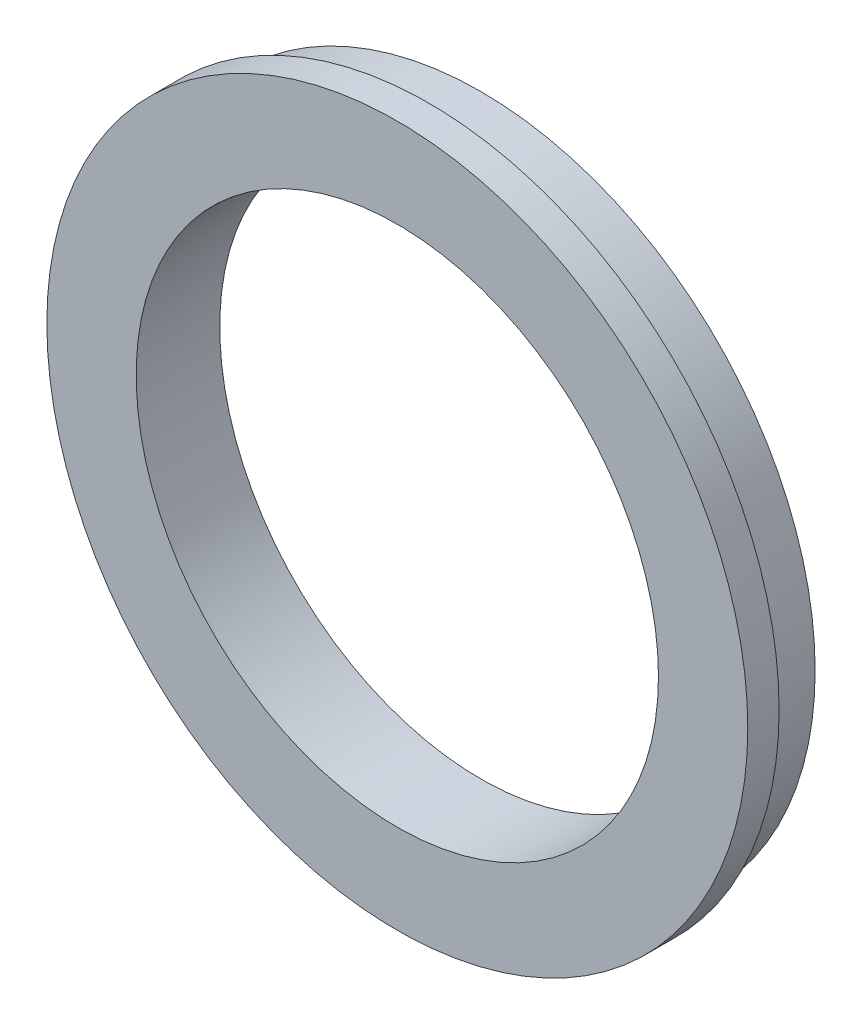
SolidWorks part; units mm, degrees
ref_plane "前视基准面" through (0, 0, 0) normal (0, 0, 1) x (1, 0, 0)
ref_plane "上视基准面" through (0, 0, 0) normal (0, 1, 0) x (1, 0, 0)
ref_plane "右视基准面" through (0, 0, 0) normal (1, 0, 0) x (0, 0, -1)
sketch "草图1" plane through (0, 0, 0) normal (0, 0, 1) x (1, 0, 0)
  circle A0 centre (0, 0) radius 12.5
  circle A1 centre (0, 0) radius 16
  dimension "D1" = 25
  dimension "D2" = 32
extrude "凸台-拉伸1" add sketch "草图1" along normal blind 4
sketch "草图2" plane through (0, 0, 4) normal (0, 0, 1) x (1, 0, 0)
  circle A0 centre (0, 0) radius 12.5
  circle A1 centre (0, 0) radius 16.775
extrude "凸台-拉伸2" add sketch "草图2" against normal blind 1.5
